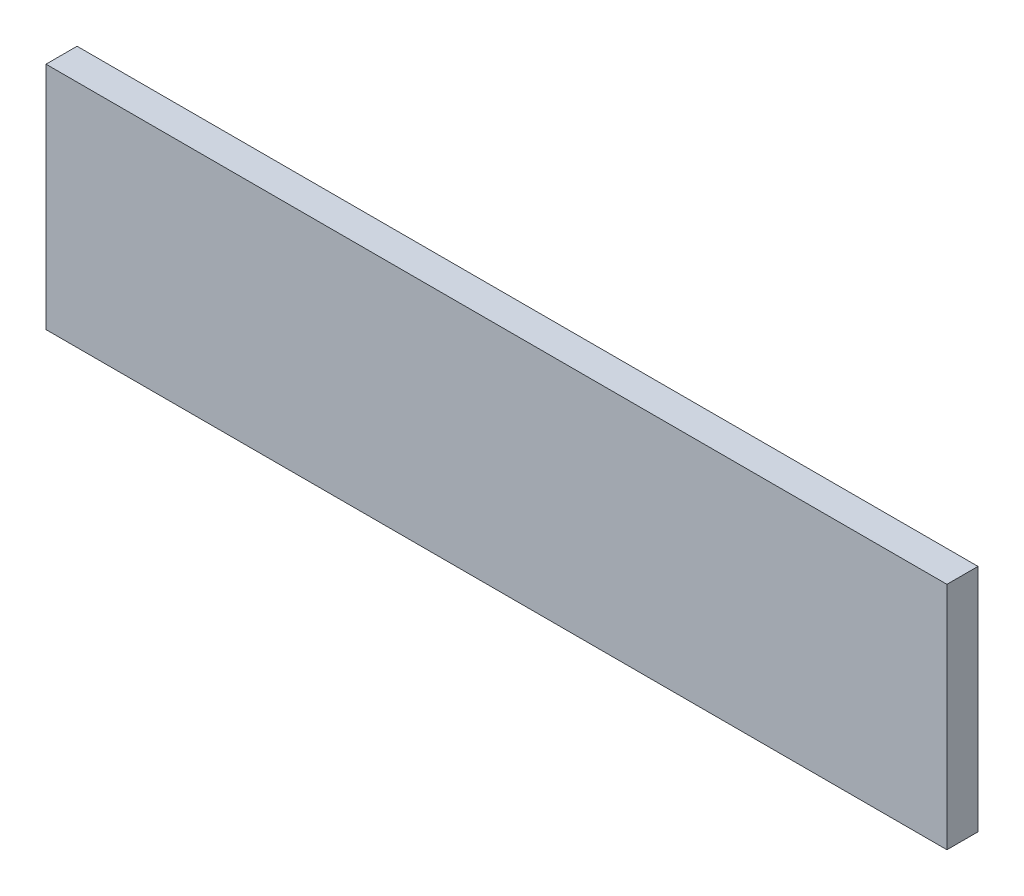
SolidWorks part; units mm, degrees
ref_plane "Front Plane" through (0, 0, 0) normal (0, 0, 1) x (1, 0, 0)
ref_plane "Top Plane" through (0, 0, 0) normal (0, 1, 0) x (1, 0, 0)
ref_plane "Right Plane" through (0, 0, 0) normal (1, 0, 0) x (0, 0, -1)
sketch "Sketch1" plane through (0, 0, 0) normal (0, 0, 1) x (1, 0, 0)
  line L0 (55, -37.7497) -> (55, 151.1829) construction
  line L1 (-90, 67) -> (200, 67)
  line L2 (-90, 67) -> (-90, -7)
  line L3 (-90, -7) -> (200, -7)
  line L4 (200, 67) -> (200, -7)
  line L7 (-70, 5) -> (-70, 65) construction
  line L8 (-67, 67) -> (177, 67) construction
  line L9 (177, -7) -> (-67, -7) construction
  point P4 (55, 67)
  dimension "D3" = 20
extrude "Boss-Extrude1" add sketch "Sketch1" along normal blind 10
